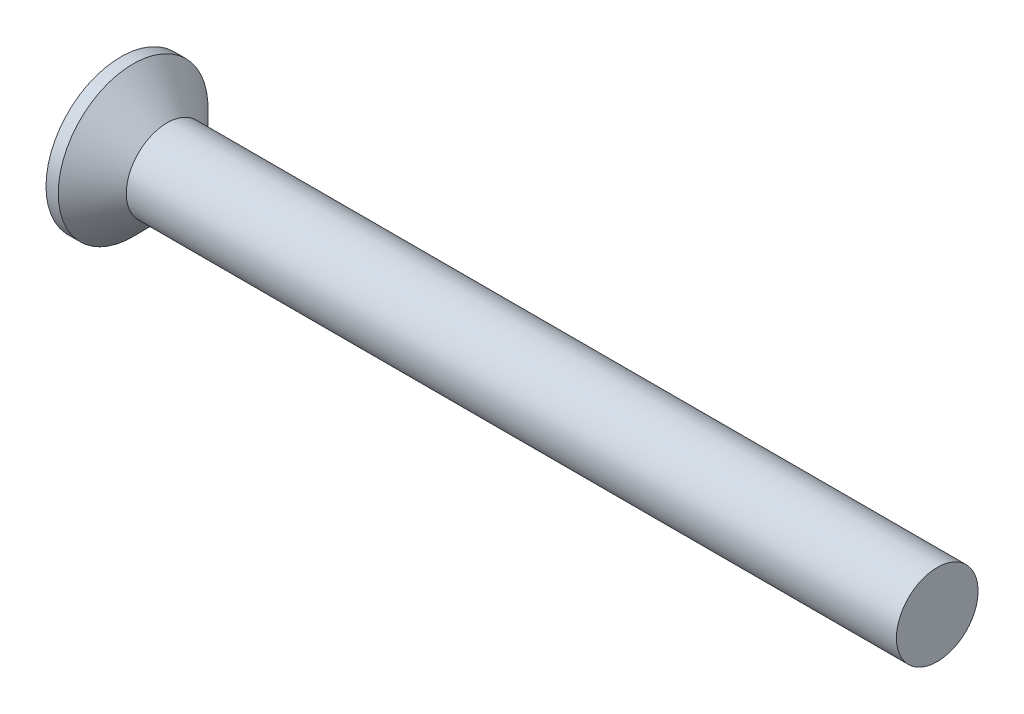
SolidWorks part; units mm, degrees
revolve "Base-Revolve" add sketch "BodySke" angle 360 about L5
sketch "BodySke" plane through (0, 0, 0) normal (0, 0, 1) x (1, 0, 0)
  line L0 (0, 0) -> (0, 2.75)
  line L1 (0, 2.75) -> (0.45, 2.75)
  line L2 (1.7, 1.5) -> (30, 1.5)
  line L3 (30, 1.5) -> (30, 0)
  line L4 (30, 0) -> (0, 0)
  line L5 (-6.35, 0) -> (82.55, 0) construction
  line L6 (1.7, -1.5) -> (30, -1.5) construction
  line L7 (0.45, -2.75) -> (1.7, -1.5) construction
  line L8 (0.45, 2.75) -> (1.7, 1.5)
  line L9 (0, -2.75) -> (0.45, -2.75) construction
  line L10 (2.2, 3.0875) -> (2.2, -6.4375) construction
  line L11 (0, 6.35) -> (0, -3.175) construction
  dimension "Head_ang" = 90
cosmetic thread "ThreadCosmetic" [suppressed] parameters "Thread_length"=3.1, "Thread_minor"=2.439
extrude "Slot" [suppressed] cut sketch "Sketch2" against normal blind 0.9
sketch "Sketch2" plane through (0, 0, 0) normal (-1, 0, 0) x (0, 0, 1)
  line L0 (-2.75, -0.5) -> (2.75, -0.5)
  line L1 (-2.75, -0.5) -> (-2.75, 0.5)
  line L2 (2.75, 0.5) -> (-2.75, 0.5)
  line L3 (2.75, 0.5) -> (2.75, -0.5)
  dimension "D1" = 0.6
  dimension "D2" = 7.3
  dimension "D3" = 3.65
ref_plane "Plane1" through (0, 0, 0) normal (0, 0, 1) x (1, 0, 0)
ref_plane "Plane2" through (0, 0, 0) normal (0, 1, 0) x (1, 0, 0)
ref_plane "Plane3" through (0, 0, 0) normal (1, 0, 0) x (0, 0, -1)
other "Configuration Table"
sketch "Sketch3" plane through (0, 0, 0) normal (-1, 0, 0) x (0, 0, 1)
  line L0 (-0.395, 1.55) -> (0.395, 1.55)
  line L1 (0.395, 1.55) -> (0.395, -1.55)
  line L2 (0.395, -1.55) -> (-0.395, -1.55)
  line L3 (-0.395, -1.55) -> (-0.395, 1.55)
  dimension "D1" = 2.03
  dimension "D2" = 0.455
ref_plane "Plane4" through (2.08, 0, 0) normal (-1, 0, 0) x (0, 0, 1)
sketch "Sketch4" plane through (2.08, 0, 0) normal (-1, 0, 0) x (0, 0, 1)
  line L0 (-0.1975, 0.1975) -> (0.1975, 0.1975)
  line L3 (0.1975, 0.1975) -> (0.1975, -0.1975)
  line L4 (0.1975, -0.1975) -> (-0.1975, -0.1975)
  line L5 (-0.1975, -0.1975) -> (-0.1975, 0.1975)
  dimension "D2" = 0.455
  dimension "D1" = 0.455
  dimension "D3" = 0.2275
  dimension "D4" = 0.2275
loft "Cross" cut profiles "Sketch3", "Sketch4"
pattern_circular "CirPattern1" count 2 every 90 about axis through (0, 0, 0) along (1, 0, 0) of "Cross"
sketch "ThdSchSke" plane through (0, 0, 0) normal (0, 0, 1) x (1, 0, 0)
  line L0 (2.2, -1.2195) -> (2.0036, -1.5)
  line L1 (2.2, -1.2195) -> (2.3964, -1.5)
  line L2 (2.3964, -1.5) -> (2.3964, -1.875)
  line L3 (-3.175, 0) -> (5.1513, 0) construction
  line L5 (2.3964, -1.875) -> (2.0036, -1.875)
  line L6 (2.0036, -1.875) -> (2.0036, -1.5)
  line L7 (0, 2.75) -> (0, -2.75) construction
  dimension "Thread_minor" = 2.829
  dimension "Diameter" = 3.5
  dimension "Start" = 2.9
revolve "ThreadSchematic" [suppressed] cut sketch "ThdSchSke" angle 360 about L3
pattern_linear "ThdSchPat" [suppressed]
equation "\"D1@Sketch3\" = \"Cross_dia@Sketch3\" / 2"
equation "\"D2@Sketch3\" = \"Cross_width@Sketch3\" / 2"
equation "\"D1@Sketch4\" = \"Cross_width@Sketch3\" *.5"
equation "\"D2@Sketch4\" = \"D1@Sketch4\""
equation "\"D4@Sketch4\" = \"D2@Sketch4\" / 2"
equation "\"D3@Sketch4\" = \"D1@Sketch4\" / 2"
equation "\"D1@Sketch2\" = \"Slot_width@Sketch2\" / 2"
equation "\"D2@Sketch2\" = \"Head_dia@BodySke\""
equation "\"D3@Sketch2\" = \"D2@Sketch2\" / 2"
equation "\"Thread_length@ThreadCosmetic\" = ((sgn( (\"Length@BodySke\" - \"Advance@BodySke\" - \"Head_ht@BodySke\" ) - \"Thread_nom@BodySke\" )-1)*( (\"Length@BodySke\" - \"Advance@BodySke\" - \"Head_ht@BodySke\" ) - \"Thread_nom@BodySke\" ))/-2+ \"Thread_nom@BodySke\""
equation "\"Thread_minor@ThdSchSke\" = \"Thread_minor@ThreadCosmetic\""
equation "\"Diameter@ThdSchSke\" = \"Diameter@BodySke\""
equation "\"Overcut@ThdSchSke\" = \"Diameter@BodySke\" * 1.25"
equation "\"Start@ThdSchSke\" = 0.000001 + \"Length@BodySke\" - \"Thread_length@ThreadCosmetic\"  '---Countersunk---"
equation "\"Num_threads@ThdSchPat\" = int( \"Thread_length@ThreadCosmetic\" / \"Advance@BodySke\" + 0.999 )  + 1"
equation "\"Advance@ThdSchPat\" = \"Thread_length@ThreadCosmetic\" /  (\"Num_threads@ThdSchPat\" - 1) 'relax it"
